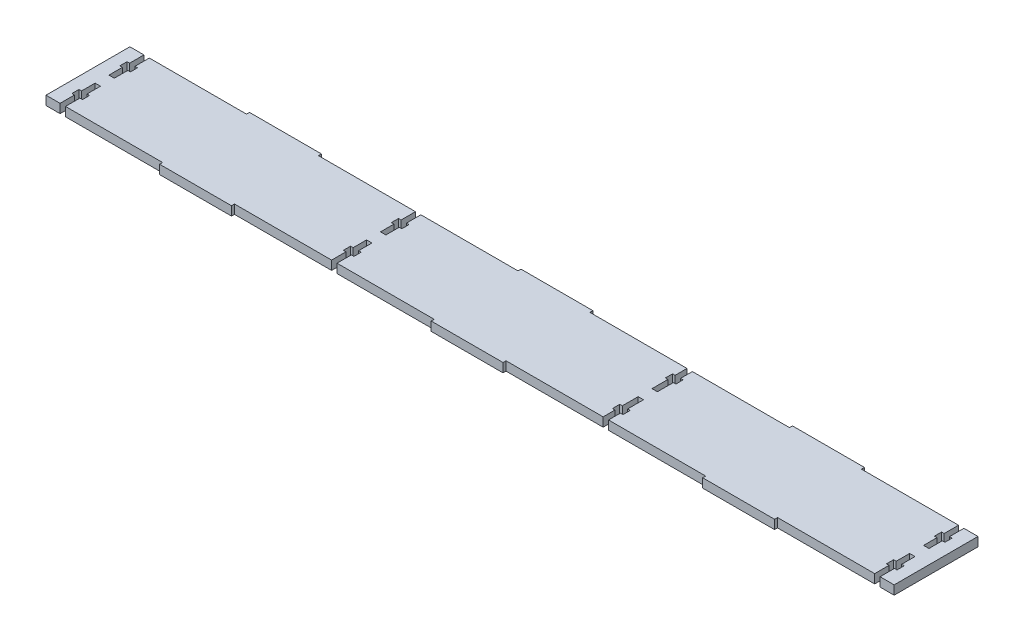
SolidWorks part; units mm, degrees
ref_plane "Front Plane" through (0, 0, 0) normal (0, 0, 1) x (1, 0, 0)
ref_plane "Top Plane" through (0, 0, 0) normal (0, 1, 0) x (1, 0, 0)
ref_plane "Right Plane" through (0, 0, 0) normal (1, 0, 0) x (0, 0, -1)
sketch "Sketch1" plane through (0, 0, 0) normal (0, 1, 0) x (1, 0, 0)
  line L1 (228.6, -23.8125) -> (-228.6, -23.8125)
  line L2 (228.6, -23.8125) -> (228.6, 23.8125)
  line L3 (228.6, 23.8125) -> (-228.6, 23.8125)
  line L4 (-228.6, -23.8125) -> (-228.6, 23.8125)
  line L5 (228.6, -23.8125) -> (-228.6, 23.8125) construction
  line L6 (228.6, 23.8125) -> (-228.6, -23.8125) construction
  point P0 (0, 0)
  dimension "D1" = 457.2
  dimension "D2" = 47.625
extrude "Boss-Extrude1" add sketch "Sketch1" along normal blind 4.7625
sketch "Sketch2" plane through (0, 0, 0) normal (0, -1, 0) x (1, 0, 0)
  line L0 (124.8833, 22.225) -> (162.9833, 22.225) construction
  line L1 (124.8833, 23.8125) -> (162.9833, 23.8125) construction
  line L2 (124.8833, 22.225) -> (124.8833, 23.8125) construction
  line L3 (162.9833, 22.225) -> (162.9833, 23.8125) construction
  line L4 (124.8833, 22.225) -> (162.9833, 22.225)
  line L5 (124.8833, 23.8125) -> (162.9833, 23.8125)
  line L6 (124.8833, 22.225) -> (124.8833, 23.8125)
  line L7 (162.9833, 22.225) -> (162.9833, 23.8125)
  line L8 (-124.8833, 22.225) -> (-124.8833, 23.8125) construction
  line L9 (-162.9833, 22.225) -> (-124.8833, 22.225) construction
  line L10 (-162.9833, 23.8125) -> (-124.8833, 23.8125) construction
  line L11 (-162.9833, 22.225) -> (-162.9833, 23.8125) construction
  line L12 (19.05, 22.225) -> (19.05, 23.8125) construction
  line L13 (-19.05, 23.8125) -> (19.05, 23.8125) construction
  line L14 (-19.05, 22.225) -> (-19.05, 23.8125) construction
  line L15 (-19.05, 22.225) -> (19.05, 22.225) construction
  line L16 (-124.8833, 22.225) -> (-124.8833, 23.8125)
  line L17 (-162.9833, 22.225) -> (-124.8833, 22.225)
  line L18 (-162.9833, 23.8125) -> (-124.8833, 23.8125)
  line L19 (-162.9833, 22.225) -> (-162.9833, 23.8125)
  line L20 (19.05, 22.225) -> (19.05, 23.8125)
  line L21 (-19.05, 23.8125) -> (19.05, 23.8125)
  line L22 (-19.05, 22.225) -> (-19.05, 23.8125)
  line L23 (-19.05, 22.225) -> (19.05, 22.225)
  line L24 (-162.9833, 22.225) -> (-228.6, 22.225)
  line L25 (-228.6, -23.8125) -> (-228.6, 23.8125) construction
  line L26 (-228.6, 22.225) -> (-228.6, 23.8125)
  line L27 (-228.6, 23.8125) -> (-162.9833, 23.8125)
  line L28 (-124.8833, 22.225) -> (-19.05, 22.225)
  line L29 (-124.8833, 23.8125) -> (-19.05, 23.8125)
  line L30 (19.05, 22.225) -> (124.8833, 22.225)
  line L31 (19.05, 23.8125) -> (124.8833, 23.8125)
  line L32 (162.9833, 22.225) -> (228.6, 22.225)
  line L33 (228.6, 23.8125) -> (228.6, -23.8125) construction
  line L34 (228.6, 22.225) -> (228.6, 23.8125)
  line L35 (228.6, 23.8125) -> (162.9833, 23.8125)
  line L36 (-228.6, 23.8125) -> (-162.9833, 23.8125)
  line L37 (162.9833, 23.8125) -> (228.6, 23.8125)
  line M1 (-228.6, 23.8125) -> (-228.6, -23.8125)
  line M3 (228.6, -23.8125) -> (228.6, 23.8125)
  line M4 (228.6, 23.8125) -> (-228.6, 23.8125)
extrude "Cut-Extrude1" cut sketch "Sketch2" against normal up to surface (4.7625 mm away) contours L24 L19 M4 M1 | L16 L28 L22 M4 | L20 L30 L6 M4 | L7 L32 M3 M4 up to face at (0, 4.7625, 0)
sketch "Sketch3" plane through (0, 0, 0) normal (0, -1, 0) x (1, 0, 0)
  line L0 (124.8833, -22.225) -> (162.9833, -22.225) construction
  line L1 (124.8833, -23.8125) -> (124.8833, -22.225) construction
  line L2 (162.9833, -23.8125) -> (124.8833, -23.8125) construction
  line L3 (162.9833, -23.8125) -> (162.9833, -22.225) construction
  line L4 (-19.05, -23.8125) -> (-19.05, -22.225) construction
  line L5 (-19.05, -22.225) -> (19.05, -22.225) construction
  line L6 (19.05, -23.8125) -> (-19.05, -23.8125) construction
  line L7 (19.05, -23.8125) -> (19.05, -22.225) construction
  line L8 (-124.8833, -23.8125) -> (-124.8833, -22.225) construction
  line L9 (-162.9833, -22.225) -> (-124.8833, -22.225) construction
  line L10 (-162.9833, -23.8125) -> (-162.9833, -22.225) construction
  line L11 (-124.8833, -23.8125) -> (-162.9833, -23.8125) construction
  line L12 (124.8833, -22.225) -> (162.9833, -22.225)
  line L13 (124.8833, -23.8125) -> (124.8833, -22.225)
  line L14 (162.9833, -23.8125) -> (124.8833, -23.8125)
  line L15 (162.9833, -23.8125) -> (162.9833, -22.225)
  line L16 (-19.05, -23.8125) -> (-19.05, -22.225)
  line L17 (-19.05, -22.225) -> (19.05, -22.225)
  line L18 (19.05, -23.8125) -> (-19.05, -23.8125)
  line L19 (19.05, -23.8125) -> (19.05, -22.225)
  line L20 (-124.8833, -23.8125) -> (-124.8833, -22.225)
  line L21 (-162.9833, -22.225) -> (-124.8833, -22.225)
  line L22 (-162.9833, -23.8125) -> (-162.9833, -22.225)
  line L23 (-124.8833, -23.8125) -> (-162.9833, -23.8125)
  line L24 (-162.9833, -23.8125) -> (-228.6, -23.8125)
  line L25 (-228.6, -23.8125) -> (-228.6, -22.225)
  line L26 (-228.6, -23.8125) -> (-228.6, 22.225) construction
  line L27 (-228.6, -22.225) -> (-162.9833, -22.225)
  line L28 (-124.8833, -23.8125) -> (-19.05, -23.8125)
  line L29 (-124.8833, -22.225) -> (-19.05, -22.225)
  line L30 (19.05, -23.8125) -> (124.8833, -23.8125)
  line L31 (124.8833, -22.225) -> (19.05, -22.225)
  line L32 (162.9833, -23.8125) -> (228.6, -23.8125)
  line L33 (228.6, -23.8125) -> (228.6, -22.225)
  line L34 (228.6, 22.225) -> (228.6, -23.8125) construction
  line L35 (228.6, -22.225) -> (162.9833, -22.225)
  line L36 (19.05, -22.225) -> (19.05, -23.8125)
  line L37 (19.05, -23.8125) -> (124.8833, -23.8125)
  line L38 (124.8833, -22.225) -> (19.05, -22.225)
  line M4 (-228.6, 22.225) -> (-228.6, -23.8125)
  line M5 (-228.6, -23.8125) -> (228.6, -23.8125)
  line M6 (228.6, -23.8125) -> (228.6, 22.225)
extrude "Cut-Extrude3" cut sketch "Sketch3" against normal up to surface (4.7625 mm away) contours L27 L22 M4 M5 | L29 L20 L16 M5 | L13 L31 L19 M5 | L35 L15 M6 M5
sketch "Sketch4" plane through (0, 4.7625, 0) normal (0, 1, 0) x (1, 0, 0)
  line L0 (162.9833, -22.225) -> (228.6, -22.225) construction
  line L1 (217.3287, -22.225) -> (214.4712, -22.225)
  line L2 (217.3287, -22.225) -> (217.3287, -14.605)
  line L3 (217.3287, -3.683) -> (214.4712, -3.683)
  line L4 (214.4712, -22.225) -> (214.4712, -14.605)
  line L5 (73.3954, -22.225) -> (73.3954, -15.9402)
  line L6 (218.694, -14.605) -> (217.3287, -14.605)
  line L7 (218.694, -14.605) -> (218.694, -10.795)
  line L8 (218.694, -10.795) -> (217.3287, -10.795)
  line L9 (213.106, -14.605) -> (213.106, -10.795)
  line L10 (73.3954, -22.225) -> (70.5379, -22.225)
  line L11 (70.5379, -22.225) -> (70.5379, -15.9402)
  line L12 (73.3954, -3.6775) -> (70.5379, -3.6775)
  line L13 (74.7607, -15.9402) -> (74.7607, -12.0946)
  line L14 (74.7607, -15.9402) -> (73.3954, -15.9402)
  line L15 (69.1727, -15.9402) -> (69.1727, -12.0946)
  line L16 (74.7607, -12.0946) -> (73.3954, -12.0946)
  line L17 (-70.5379, -22.225) -> (-70.5379, -14.605)
  line L18 (-70.5379, -22.225) -> (-73.3954, -22.225)
  line L19 (-73.3954, -22.225) -> (-73.3954, -14.605)
  line L20 (-70.5379, -3.683) -> (-73.3954, -3.683)
  line L21 (-69.1727, -14.605) -> (-69.1727, -10.795)
  line L22 (-69.1727, -14.605) -> (-70.5379, -14.605)
  line L23 (-74.7607, -14.605) -> (-74.7607, -10.795)
  line L24 (-69.1727, -10.795) -> (-70.5379, -10.795)
  line L25 (-214.4713, -22.225) -> (-214.4713, -14.605)
  line L26 (-214.4713, -22.225) -> (-217.3288, -22.225)
  line L27 (-217.3288, -22.225) -> (-217.3288, -14.605)
  line L28 (-214.4713, -3.683) -> (-217.3288, -3.683)
  line L29 (-213.106, -14.605) -> (-213.106, -10.795)
  line L30 (-213.106, -14.605) -> (-214.4713, -14.605)
  line L31 (-218.694, -14.605) -> (-218.694, -10.795)
  line L32 (-213.106, -10.795) -> (-214.4713, -10.795)
  line L33 (71.9667, -22.225) -> (215.9, -22.225) construction
  line L34 (228.6, 0) -> (-228.6, 0) construction
  line L35 (228.6, -22.225) -> (228.6, 22.225) construction
  line L36 (-228.6, 22.225) -> (-228.6, -22.225) construction
  line L37 (-214.4713, 22.225) -> (-217.3288, 22.225)
  line L38 (-217.3288, 22.225) -> (-217.3288, 14.605)
  line L39 (-214.4713, 3.683) -> (-217.3288, 3.683)
  line L40 (-214.4713, 22.225) -> (-214.4713, 14.605)
  line L41 (-213.106, 14.605) -> (-214.4713, 14.605)
  line L42 (-218.694, 14.605) -> (-218.694, 10.795)
  line L43 (-213.106, 10.795) -> (-214.4713, 10.795)
  line L44 (-213.106, 14.605) -> (-213.106, 10.795)
  line L45 (-69.1727, 14.605) -> (-70.5379, 14.605)
  line L46 (-74.7607, 14.605) -> (-74.7607, 10.795)
  line L47 (-69.1727, 10.795) -> (-70.5379, 10.795)
  line L48 (-69.1727, 14.605) -> (-69.1727, 10.795)
  line L49 (-70.5379, 22.225) -> (-73.3954, 22.225)
  line L50 (-73.3954, 22.225) -> (-73.3954, 14.605)
  line L51 (-70.5379, 3.683) -> (-73.3954, 3.683)
  line L52 (-70.5379, 22.225) -> (-70.5379, 14.605)
  line L53 (74.7607, 15.9402) -> (73.3954, 15.9402)
  line L54 (69.1727, 15.9402) -> (69.1727, 12.0946)
  line L55 (74.7607, 12.0946) -> (73.3954, 12.0946)
  line L56 (74.7607, 15.9402) -> (74.7607, 12.0946)
  line L57 (73.3954, 22.225) -> (70.5379, 22.225)
  line L58 (70.5379, 22.225) -> (70.5379, 15.9402)
  line L59 (73.3954, 3.6775) -> (70.5379, 3.6775)
  line L60 (73.3954, 22.225) -> (73.3954, 15.9402)
  line L61 (218.694, 10.795) -> (217.3287, 10.795)
  line L62 (213.106, 14.605) -> (213.106, 10.795)
  line L63 (218.694, 14.605) -> (217.3287, 14.605)
  line L64 (218.694, 14.605) -> (218.694, 10.795)
  line L65 (217.3287, 3.683) -> (214.4712, 3.683)
  line L66 (217.3287, 22.225) -> (214.4712, 22.225)
  line L67 (217.3287, 22.225) -> (217.3287, 14.605)
  line L68 (214.4712, 22.225) -> (214.4712, 14.605)
  line L69 (214.4712, 10.795) -> (213.106, 10.795)
  line L70 (214.4712, 14.605) -> (213.106, 14.605)
  line L71 (217.3287, 10.795) -> (217.3287, 3.683)
  line L72 (214.4712, 10.795) -> (214.4712, 3.683)
  line L73 (217.3287, -10.795) -> (217.3287, -3.683)
  line L74 (214.4712, -14.605) -> (213.106, -14.605)
  line L75 (214.4712, -10.795) -> (214.4712, -3.683)
  line L76 (214.4712, -10.795) -> (213.106, -10.795)
  line L77 (70.5379, -15.9402) -> (69.1727, -15.9402)
  line L78 (73.3954, -12.0946) -> (73.3954, -3.6775)
  line L79 (70.5379, -12.0946) -> (69.1727, -12.0946)
  line L80 (70.5379, -12.0946) -> (70.5379, -3.6775)
  line L81 (70.5379, 12.0946) -> (69.1727, 12.0946)
  line L82 (73.3954, 12.0946) -> (73.3954, 3.6775)
  line L83 (70.5379, 15.9402) -> (69.1727, 15.9402)
  line L84 (70.5379, 12.0946) -> (70.5379, 3.6775)
  line L85 (-73.3954, -14.605) -> (-74.7607, -14.605)
  line L86 (-70.5379, -10.795) -> (-70.5379, -3.683)
  line L87 (-73.3954, -10.795) -> (-74.7607, -10.795)
  line L88 (-73.3954, -10.795) -> (-73.3954, -3.683)
  line L89 (-73.3954, 10.795) -> (-74.7607, 10.795)
  line L90 (-70.5379, 10.795) -> (-70.5379, 3.683)
  line L91 (-73.3954, 14.605) -> (-74.7607, 14.605)
  line L92 (-73.3954, 10.795) -> (-73.3954, 3.683)
  line L93 (-217.3288, -14.605) -> (-218.694, -14.605)
  line L94 (-214.4713, -10.795) -> (-214.4713, -3.683)
  line L95 (-217.3288, -10.795) -> (-217.3288, -3.683)
  line L96 (-217.3288, -10.795) -> (-218.694, -10.795)
  line L97 (-217.3288, 10.795) -> (-218.694, 10.795)
  line L98 (-214.4713, 10.795) -> (-214.4713, 3.683)
  line L99 (-217.3288, 14.605) -> (-218.694, 14.605)
  line L100 (-217.3288, 10.795) -> (-217.3288, 3.683)
  line L101 (217.3287, -14.605) -> (217.3287, -10.795) construction
  line L102 (217.3287, -10.795) -> (214.4712, -10.795) construction
  line L103 (214.4712, -10.795) -> (214.4712, -14.605) construction
  line L104 (214.4712, -14.605) -> (217.3287, -14.605) construction
  line L105 (213.106, 12.7) -> (218.694, 12.7) construction
  point P0 (-215.9, -23.8125)
  point P2 (71.9667, -23.8125)
  point P4 (215.9, -23.8125)
  point P6 (-71.9667, -23.8125)
  point P14 (215.9, -22.225)
  point P118 (-215.9, -22.225)
  point P119 (-71.9667, -22.225)
  dimension "D1" = 2.8575
  dimension "D2" = 18.542
  dimension "D3" = 5.588
  dimension "D4" = 3.81
  dimension "D5" = 7.62
  dimension "D7" = 143.9333
extrude "Cut-Extrude4" cut sketch "Sketch4" against normal up to surface (4.7625 mm away) up to face at (0, 0, 0)
sketch "Sketch6" plane through (0, 4.7625, 0) normal (0, 1, 0) x (1, 0, 0)
  line L0 (-228.6, 0) -> (228.6, 0) construction
  line L1 (-228.6, 22.225) -> (-228.6, -22.225) construction
  line L2 (228.6, -22.225) -> (228.6, 22.225) construction
  line L3 (0, -23.8125) -> (0, 23.8125) construction
  line L4 (19.05, 23.8125) -> (-19.05, 23.8125) construction
  line L5 (-217.3288, -22.225) -> (-228.6, -22.225) construction
  line L6 (-228.6, 22.225) -> (-224.79, 22.225)
  line L7 (-228.6, 22.225) -> (-228.6, -22.225)
  line L8 (-228.6, -22.225) -> (-224.79, -22.225)
  line L9 (-224.79, 22.225) -> (-224.79, -22.225)
  line L10 (228.6, -22.225) -> (224.79, -22.225)
  line L11 (224.79, 22.225) -> (224.79, -22.225)
  line L12 (228.6, 22.225) -> (224.79, 22.225)
  line L13 (228.6, 22.225) -> (228.6, -22.225)
  point P11 (0, 0)
  dimension "D1" = 3.81
extrude "Cut-Extrude6" cut sketch "Sketch6" against normal up to surface (4.7625 mm away) up to face at (0, 0, 0)
equation "\"sheetthickness\"= 3 / 16"
equation "\"D1@Boss-Extrude1\"=\"sheetthickness\""
